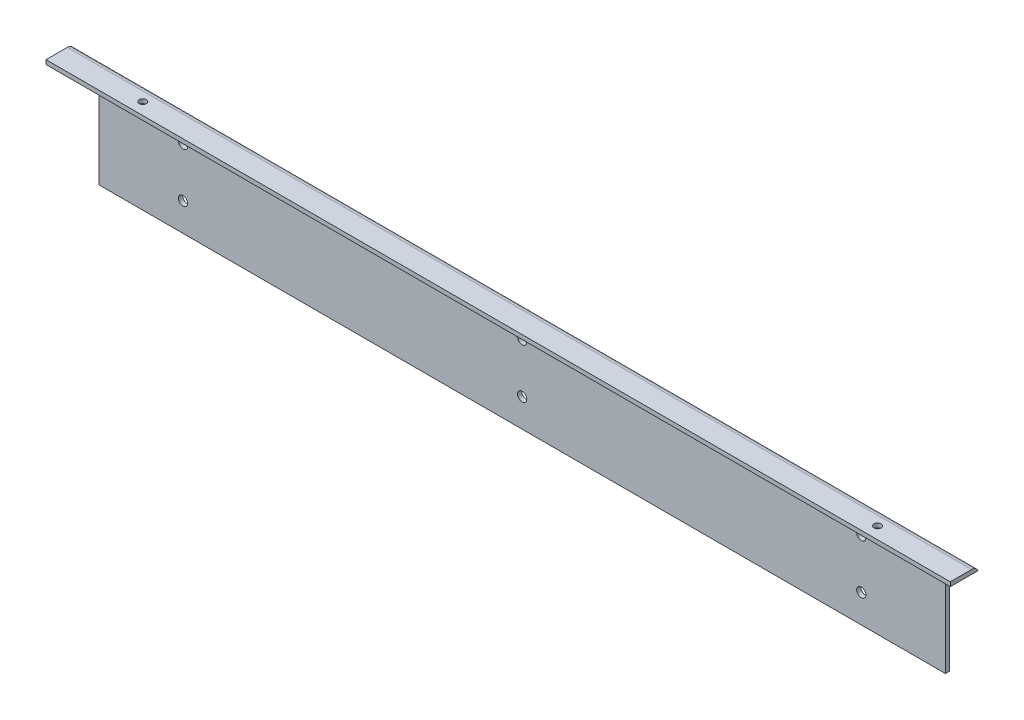
SolidWorks part; units mm, degrees
ref_plane "정면" through (0, 0, 0) normal (0, 0, 1) x (1, 0, 0)
ref_plane "윗면" through (0, 0, 0) normal (0, 1, 0) x (1, 0, 0)
ref_plane "우측면" through (0, 0, 0) normal (1, 0, 0) x (0, 0, -1)
sketch "스케치1" plane through (0, 0, 0) normal (0, 0, 1) x (1, 0, 0)
  line L1 (0, 0) -> (640, 0)
  line L2 (0, 0) -> (0, 75)
  line L3 (0, 75) -> (640, 75)
  line L4 (640, 0) -> (640, 75)
  dimension "D1" = 640
  dimension "D2" = 75
extrude "보스-돌출1" add sketch "스케치1" along normal blind 3
sketch "스케치2" plane through (0, 0, 3) normal (0, 0, 1) x (1, 0, 0)
  line L0 (640, 0) -> (640, 75) construction
  line L1 (0, 75) -> (640, 75)
  line L2 (0, 75) -> (0, 72)
  line L3 (0, 72) -> (640, 72)
  line L4 (640, 75) -> (640, 72)
  dimension "D1" = 3
extrude "보스-돌출2" add sketch "스케치2" along normal blind 17
fillet "필렛1" radius 5 1 edges at (320, 75, 0)
sketch "스케치5" plane through (0, 72, 0) normal (0, -1, 0) x (1, 0, 0)
  line L0 (0, 20) -> (640, 20) construction
  line L2 (0, 20) -> (0, 3) construction
  circle A0 centre (60, 11.5) radius 2.5
  circle A1 centre (580, 11.5) radius 2.5
  point P6 (0, 0)
  dimension "D4" = 5
  dimension "D1" = 8.5
  dimension "D2" = 60
  dimension "D3" = 520
extrude "컷-돌출3" cut sketch "스케치5" against normal through all
sketch "스케치3" plane through (0, 0, 3) normal (0, 0, 1) x (1, 0, 0)
  line L0 (0, 72) -> (0, 0) construction
  line L1 (0, 0) -> (640, 0) construction
  circle A0 centre (80, 55) radius 3.25
  circle A1 centre (80, 20) radius 3.25
  circle A2 centre (320, 55) radius 3.25
  circle A3 centre (320, 20) radius 3.25
  circle A4 centre (560, 55) radius 3.25
  circle A5 centre (560, 20) radius 3.25
  point P14 (0, 0)
  point P15 (0, 0)
  point P16 (0, 0)
  point P17 (0, 0)
  point P20 (0, 0)
  point P21 (0, 0)
  dimension "D4" = 6.5
  dimension "D1" = 80
  dimension "D2" = 240
  dimension "D3" = 240
  dimension "D5" = 20
  dimension "D6" = 35
extrude "컷-돌출1" cut sketch "스케치3" against normal through all
sketch "스케치4" plane through (0, 0, 3) normal (0, 0, 1) x (1, 0, 0)
  line L0 (0, 0) -> (640, 0) construction
  line L1 (20.5, 0) -> (0, 0)
  line L2 (20.5, 0) -> (20.5, 72)
  line L3 (20.5, 72) -> (0, 72)
  line L4 (0, 0) -> (0, 72)
  line L5 (0, 72) -> (640, 72) construction
  line L6 (640, 0) -> (619.5, 0)
  line L7 (640, 0) -> (640, 72)
  line L8 (640, 72) -> (619.5, 72)
  line L9 (619.5, 0) -> (619.5, 72)
  dimension "D1" = 20.5
  dimension "D2" = 599
extrude "컷-돌출2" cut sketch "스케치4" against normal through all
fillet "필렛3" radius 2 1 edges at (320, 72, 3)
